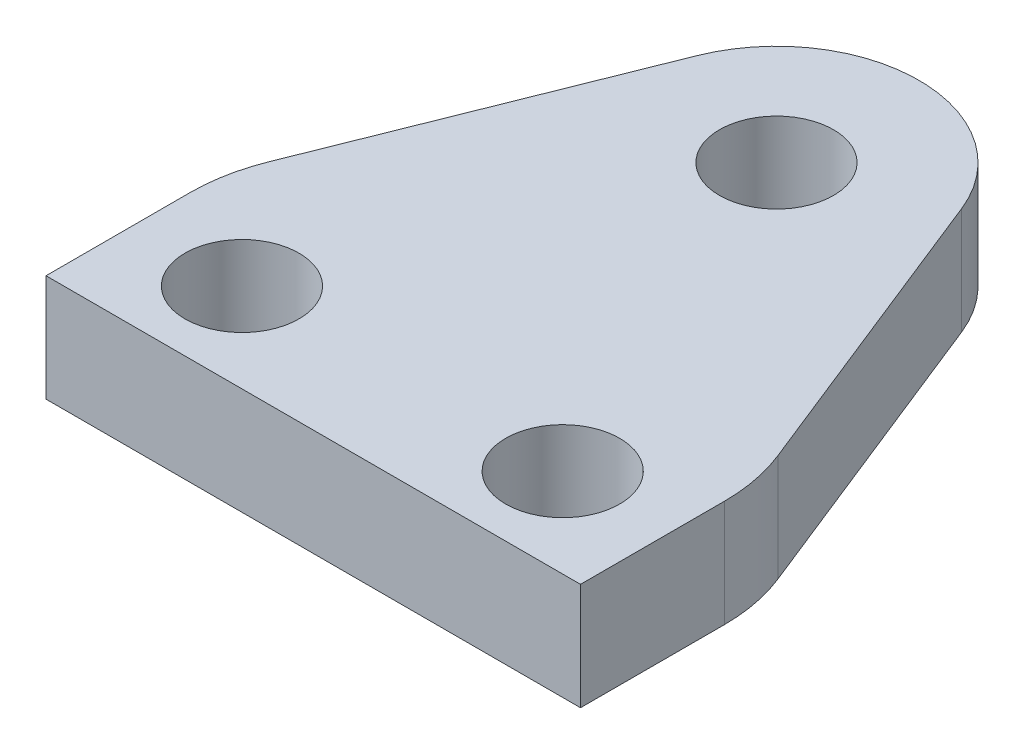
SolidWorks part; units mm, degrees
ref_plane "Front Plane" through (0, 0, 0) normal (0, 0, 1) x (1, 0, 0)
ref_plane "Top Plane" through (0, 0, 0) normal (0, 1, 0) x (1, 0, 0)
ref_plane "Right Plane" through (0, 0, 0) normal (1, 0, 0) x (0, 0, -1)
sketch "Sketch1" plane through (0, 0, 0) normal (0, 1, 0) x (1, 0, 0)
  line L0 (7.5, 5) -> (7.5, 13) construction
  line L1 (0, 0) -> (15, 0)
  line L2 (0, 0) -> (0, 5)
  line L3 (0, 5) -> (15, 5) construction
  line L4 (15, 0) -> (15, 5)
  line L5 (0, 5) -> (3.785, 14.4828)
  line L6 (0, 2.5) -> (15, 2.5) construction
  line L8 (11.215, 14.4828) -> (15, 5)
  circle A0 centre (3, 2.5) radius 1.6
  circle A1 centre (12, 2.5) radius 1.6
  circle A2 centre (7.5, 13) radius 1.6
  circle A3 centre (7.5, 13) radius 4
  dimension "D4" = 3.2
  dimension "D5" = 3
  dimension "D6" = 3
  dimension "D7" = 3.2
  dimension "D8" = 8
  dimension "D1" = 15
  dimension "D2" = 8
  dimension "D3" = 5
extrude "Boss-Extrude1" add sketch "Sketch1" along normal blind 3 contours A3 L5 L2 L1 L4 L8 A1 A0 | A3 A2
fillet "Fillet1" radius 5 2 edges at (15, 1.5, -5) (0, 1.5, -5)
